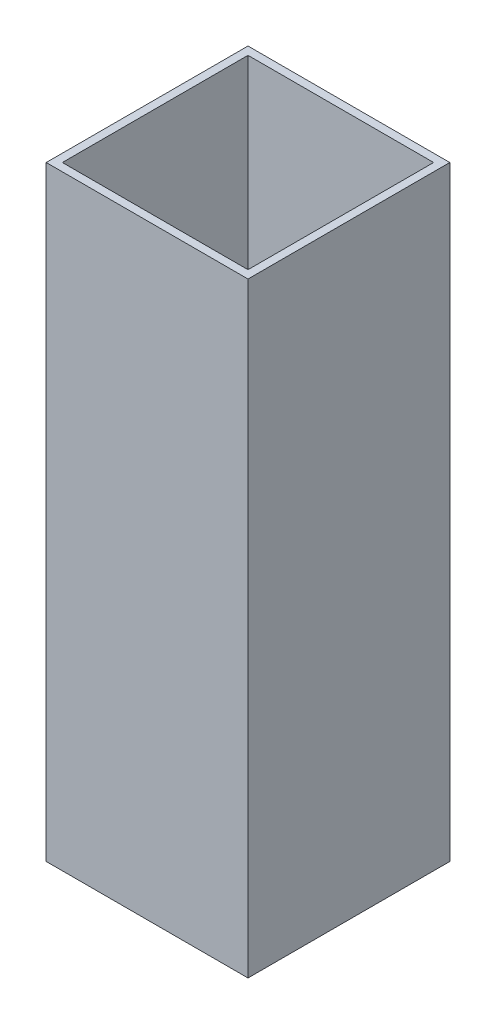
SolidWorks part; units mm, degrees
ref_plane "Front Plane" through (0, 0, 0) normal (0, 0, 1) x (1, 0, 0)
ref_plane "Top Plane" through (0, 0, 0) normal (0, 1, 0) x (1, 0, 0)
ref_plane "Right Plane" through (0, 0, 0) normal (1, 0, 0) x (0, 0, -1)
sketch "Sketch1" plane through (0, 0, 0) normal (0, 1, 0) x (1, 0, 0)
  line L0 (-23, 23) -> (23, 23)
  line L1 (-25, -25) -> (25, -25)
  line L2 (-25, -25) -> (-25, 25)
  line L3 (-25, 25) -> (25, 25)
  line L4 (25, -25) -> (25, 25)
  line L5 (-25, -25) -> (25, 25) construction
  line L6 (-25, 25) -> (25, -25) construction
  line L7 (23, -23) -> (23, 23)
  line L8 (-23, -23) -> (23, -23)
  line L9 (-23, -23) -> (-23, 23)
  point P0 (0, 0)
  dimension "D1" = 50
  dimension "D2" = 2
extrude "Boss-Extrude1" add sketch "Sketch1" along normal blind 150
